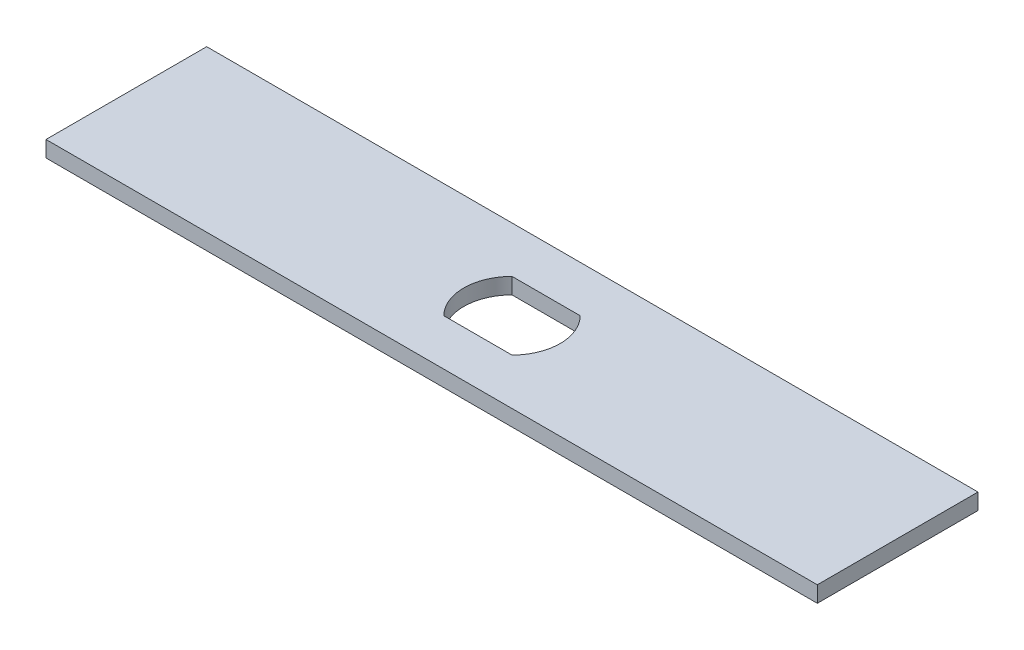
SolidWorks part; units mm, degrees
ref_plane "Front Plane" through (0, 0, 0) normal (0, 0, 1) x (1, 0, 0)
ref_plane "Top Plane" through (0, 0, 0) normal (0, 1, 0) x (1, 0, 0)
ref_plane "Right Plane" through (0, 0, 0) normal (1, 0, 0) x (0, 0, -1)
sketch "Sketch1" plane through (0, 0, 0) normal (0, 1, 0) x (1, 0, 0)
  line L1 (0, 0) -> (304.8, 0)
  line L2 (0, 0) -> (0, 63.5)
  line L3 (0, 63.5) -> (304.8, 63.5)
  line L4 (304.8, 0) -> (304.8, 63.5)
  line L5 (165.8704, 45.2204) -> (138.9296, 45.2204)
  line L6 (165.8704, 18.2796) -> (138.9296, 18.2796)
  circle A0 centre (152.4, 31.75) radius 19.05
  arc A1 (171.45, 31.75) -> (165.8704, 45.2204) centre (152.4, 31.75) ccw
  arc A2 (133.35, 31.75) -> (138.9296, 45.2204) centre (152.4, 31.75) cw
  arc A3 (171.45, 31.75) -> (165.8704, 18.2796) centre (152.4, 31.75) cw
  dimension "D1" = 304.8
  dimension "D2" = 63.5
extrude "Boss-Extrude1" add sketch "Sketch1" along normal blind 6.35 contours L1 L4 L3 L2 A0 | L5 A0 | L6 A0
